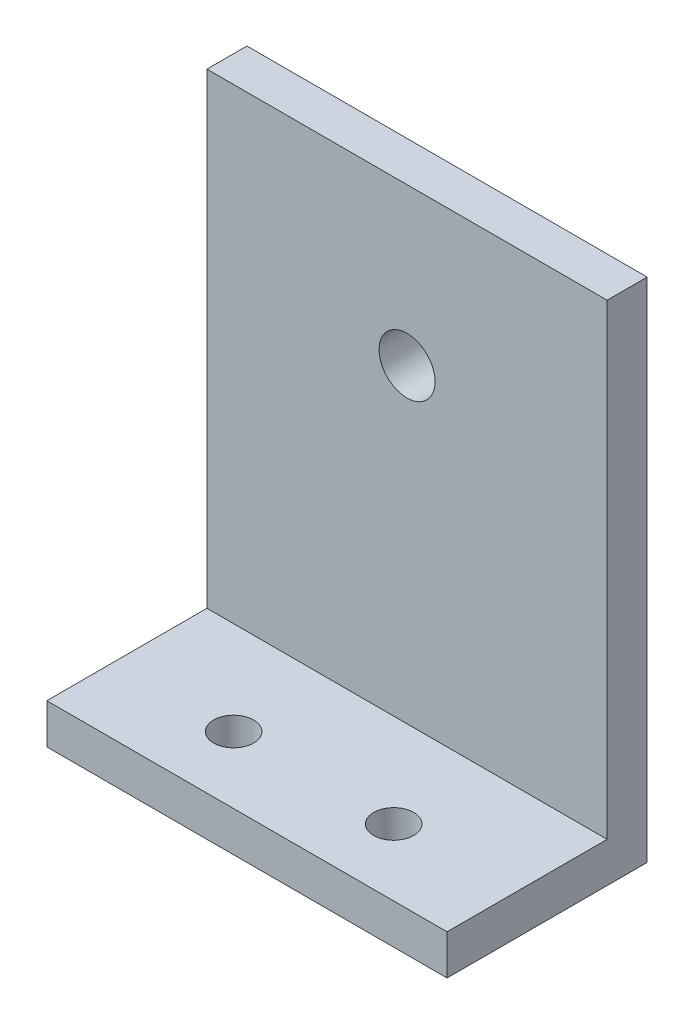
SolidWorks part; units mm, degrees
material "6063-O"
ref_plane "Front" through (0, 0, 0) normal (0, 0, 1) x (1, 0, 0)
ref_plane "Top" through (0, 0, 0) normal (0, 1, 0) x (1, 0, 0)
ref_plane "Right" through (0, 0, 0) normal (1, 0, 0) x (0, 0, -1)
sketch "草图1" plane through (0, 0, 0) normal (1, 0, 0) x (0, 0, -1)
  line L0 (0, 0) -> (0, 35)
  line L1 (0, 35) -> (3, 35)
  line L2 (3, 35) -> (3, -3)
  line L3 (0, 0) -> (-35, 0)
  line L4 (-35, 0) -> (-35, -3)
  line L5 (-35, -3) -> (3, -3)
  dimension "D1" = 35
  dimension "D2" = 3
  dimension "D3" = 38
  dimension "D4" = 35
extrude "凸台-拉伸1" add sketch "草图1" along normal blind 30
sketch "草图2" plane through (0, 0, 0) normal (0, 1, 0) x (1, 0, 0)
  line L0 (15, 0) -> (15, -35) construction
  line L1 (30, 0) -> (0, 0) construction
  line L2 (30, -35) -> (0, -35) construction
  line L3 (30, 3) -> (0, 3) construction
  line L4 (0, -35) -> (0, -25)
  line L5 (0, 0) -> (0, -35) construction
  line L6 (0, -25) -> (30, -25)
  line L7 (30, 0) -> (30, -35) construction
  line L8 (30, -25) -> (30, -35)
  line L9 (30, -35) -> (0, -35)
  circle A0 centre (9, -7) radius 1.5
  circle A1 centre (9, -19) radius 1.5
  circle A2 centre (21, -19) radius 1.5
  circle A3 centre (21, -7) radius 1.5
  dimension "D1" = 3
  dimension "D2" = 3
  dimension "D3" = 6
  dimension "D4" = 10
  dimension "D5" = 12
  dimension "D6" = 10
extrude "切除-拉伸1" cut sketch "草图2" against normal up to next
sketch "草图3" plane through (0, 0, 0) normal (0, 0, 1) x (1, 0, 0)
  line L0 (0, 35) -> (0, 0) construction
  line L1 (0, -3) -> (30, -3) construction
  circle A0 centre (15, 23.25) radius 2.1
  dimension "D1" = 4.2
  dimension "D2" = 15
  dimension "D3" = 26.25
extrude "切除-拉伸2" cut sketch "草图3" against normal through all
sketch "草图4" plane through (0, 0, 25) normal (0, 0, 1) x (1, 0, 0)
  line L4 (0, -3) -> (30, -3)
  line L5 (30, -3) -> (30, 0)
  line L6 (30, 0) -> (0, 0)
  line L7 (0, 0) -> (0, -3)
  line L8 (0, -3) -> (30, -3)
  line L9 (30, -3) -> (30, 0)
  line L10 (30, 0) -> (0, 0)
  line L11 (0, 0) -> (0, -3)
  dimension "D1" = 0
extrude "切除-拉伸3" cut sketch "草图4" against normal blind 13
sketch "草图5" plane through (0, 0, 0) normal (0, 0, 1) x (1, 0, 0)
  line L0 (0, 20) -> (15, 35)
  line L1 (0, 35) -> (0, 0) construction
  line L2 (30, 35) -> (0, 35) construction
  line L3 (15, 35) -> (30, 20)
  line L4 (30, 35) -> (30, 0) construction
  line L5 (30, 20) -> (30, 35)
  line L6 (30, 35) -> (0, 35)
  line L7 (0, 35) -> (0, 20)
  line L8 (7.5, 27.5) -> (22.5, 27.5)
  line M3 (0, 35) -> (0, 0)
  line M5 (30, 0) -> (30, 35)
  line M6 (30, 35) -> (0, 35)
  dimension "D1" = 15
extrude "切除-拉伸4" [suppressed] cut sketch "草图5" against normal through all and the other way through all contours L0 M3 M6 | L0 L8 L3 | L3 M6 M5
fillet "圆角1" [suppressed] radius 3
